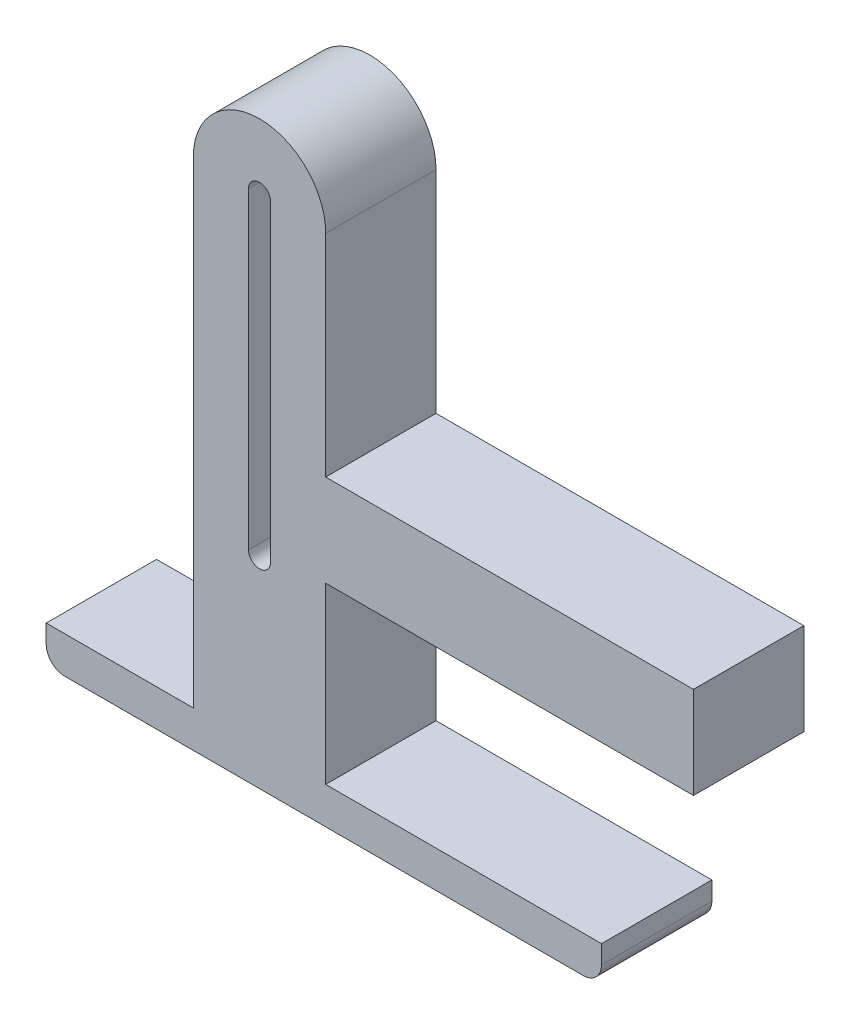
SolidWorks part; units mm, degrees
ref_plane "Front Plane" through (0, 0, 0) normal (0, 0, 1) x (1, 0, 0)
ref_plane "Top Plane" through (0, 0, 0) normal (0, 1, 0) x (1, 0, 0)
ref_plane "Right Plane" through (0, 0, 0) normal (1, 0, 0) x (0, 0, -1)
sketch "Sketch1" plane through (0, 0, 0) normal (0, 0, 1) x (1, 0, 0)
  line L0 (0, 0) -> (0, 17) construction
  line L1 (-0.6, 0) -> (-0.6, 17)
  line L2 (0.6, 0) -> (0.6, 17)
  line L3 (-3.6, 0) -> (-3.6, 17)
  line L4 (3.6, 0) -> (3.6, 17)
  line L5 (-3.6, 0) -> (3.6, 0) construction
  line L6 (3.6, 0) -> (3.6, -10.9543)
  line L7 (3.6, -10.9543) -> (-3.6, -10.9543)
  line L8 (-3.6, -10.9543) -> (-3.6, 0)
  arc A0 (-0.6, 0) -> (0.6, 0) centre (0, 0) ccw
  arc A1 (0.6, 17) -> (-0.6, 17) centre (0, 17) ccw
  arc A2 (3.6, 17) -> (-3.6, 17) centre (0, 17) ccw
  point P2 (0, 8.5)
  dimension "D2" = 10.9543
  dimension "D3" = 3.6
  dimension "D5" = 0.6
  dimension "D1" = 3
  dimension "D4" = 17
extrude "Boss-Extrude1" add sketch "Sketch1" along normal blind 6
sketch "Sketch2" plane through (3.6, 0, 0) normal (1, 0, 0) x (0, 0, -1)
  line L0 (-3, 17) -> (-3, -10.9543) construction
  line L1 (-6, 17) -> (0, 17) construction
  line L3 (-6, 3.0228) -> (0, 3.0228) construction
  line L4 (-6, -10.9543) -> (-6, 17) construction
  line L5 (0, -10.9543) -> (0, 17) construction
  line L6 (-6, -10.9543) -> (0, -10.9543) construction
  line L7 (-6, 0.5228) -> (0, 0.5228)
  line L8 (-6, 0.5228) -> (-6, 5.5228)
  line L9 (-6, 5.5228) -> (0, 5.5228)
  line L10 (0, 0.5228) -> (0, 5.5228)
  line L11 (-6, 0.5228) -> (0, 5.5228) construction
  line L12 (-6, 5.5228) -> (0, 0.5228) construction
  point P12 (-3, 3.0228)
  dimension "D1" = 5
extrude "Boss-Extrude2" add sketch "Sketch2" along normal blind 20
sketch "Эскиз1" plane through (0, 5.5228, 0) normal (0, 1, 0) x (1, 0, 0)
  line L0 (23.6, -3) -> (3.6, -3) construction
  line L1 (23.6, 0) -> (23.6, -6) construction
  line L2 (3.6, 0) -> (3.6, -6) construction
  line L3 (13.6, 0) -> (13.6, -6) construction
  line L4 (23.6, 0) -> (3.6, 0) construction
  line L5 (23.6, -6) -> (3.6, -6) construction
  dimension "D1" = 10
sketch "Эскиз2" plane through (3.6, 0, 0) normal (1, 0, 0) x (0, 0, -1)
  line L0 (-6, -10.9543) -> (-6, 0.5228) construction
  line L1 (-6, -8.9543) -> (0, -8.9543)
  line L2 (-6, -8.9543) -> (-6, -10.9543)
  line L3 (-6, -10.9543) -> (0, -10.9543)
  line L4 (0, -8.9543) -> (0, -10.9543)
  dimension "D1" = 2
extrude "Бобышка-Вытянуть1" add sketch "Эскиз2" along normal blind 15 and the other way blind 15.2
fillet "Скругление3" radius 1 2 edges at (18.6, -10.9543, 3) (-11.6, -10.9543, 3)
